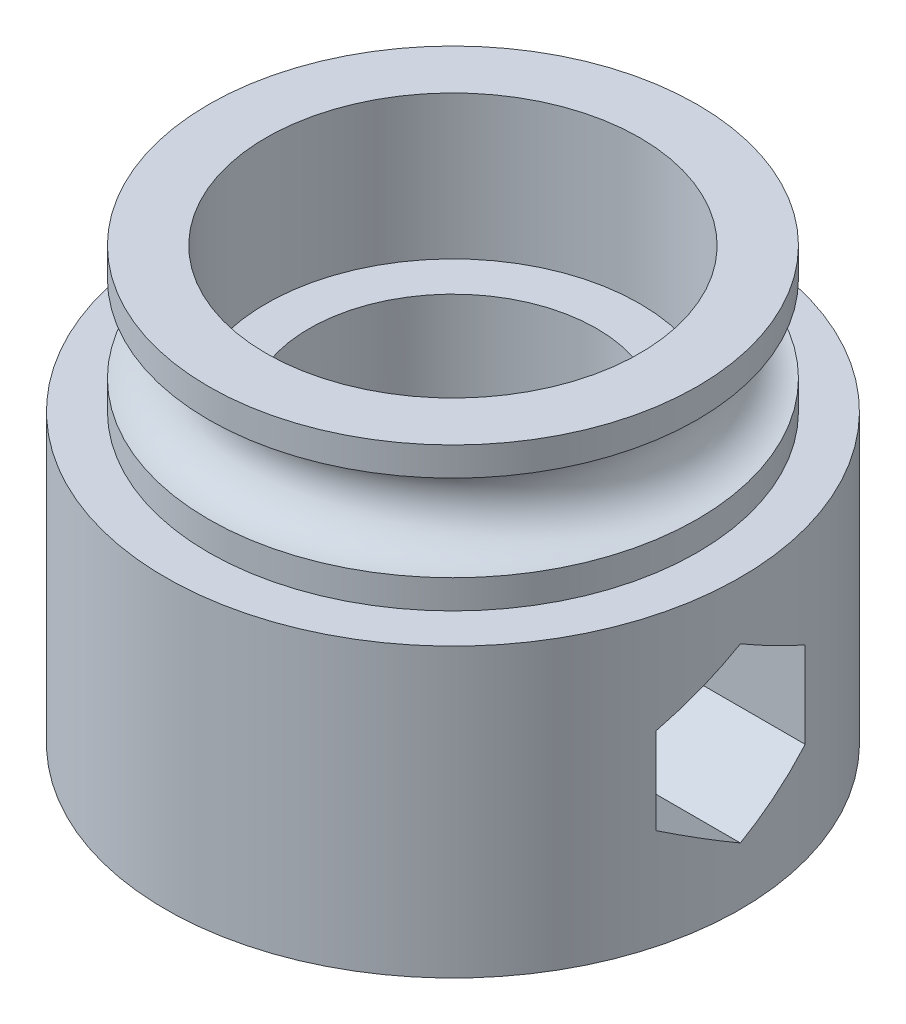
SolidWorks part; units mm, degrees
ref_plane "Front Plane" through (0, 0, 0) normal (0, 0, 1) x (1, 0, 0)
ref_plane "Top Plane" through (0, 0, 0) normal (0, 1, 0) x (1, 0, 0)
ref_plane "Right Plane" through (0, 0, 0) normal (1, 0, 0) x (0, 0, -1)
sketch "Sketch1" plane through (0, 0, 0) normal (0, 0, 1) x (1, 0, 0)
  line L0 (12.7, 0) -> (12.7, 0)
  line L1 (12.7, 0) -> (12.7, 25.4)
  line L2 (12.7, 25.4) -> (16.51, 25.4)
  line L3 (16.51, 25.4) -> (16.51, 38.1)
  line L4 (16.51, 38.1) -> (21.59, 38.1)
  line L5 (21.59, 38.1) -> (21.59, 35.56)
  line L6 (21.59, 27.94) -> (21.59, 25.4)
  line L7 (21.59, 25.4) -> (25.4, 25.4)
  line L8 (25.4, 25.4) -> (25.4, 0)
  line L9 (12.7, 0) -> (25.4, 0)
  line L10 (0, 0) -> (0, 13.7582)
  arc A0 (21.59, 35.56) -> (21.59, 27.94) centre (21.59, 31.75) ccw
revolve "Revolve1" add sketch "Sketch1" angle 360 about L10
sketch "Sketch2" plane through (0, 0, 0) normal (1, 0, 0) x (0, 0, -1)
  line L1 (0, 20.32) -> (-6.5991, 16.51)
  line L2 (-6.5991, 16.51) -> (-6.5991, 8.89)
  line L3 (-6.5991, 8.89) -> (0, 5.08)
  line L4 (0, 5.08) -> (6.5991, 8.89)
  line L5 (6.5991, 8.89) -> (6.5991, 16.51)
  line L6 (6.5991, 16.51) -> (0, 20.32)
  circle A0 centre (0, 12.7) radius 7.62 construction
extrude "Cut-Extrude1" cut sketch "Sketch2" against normal through all both and the other way through all
